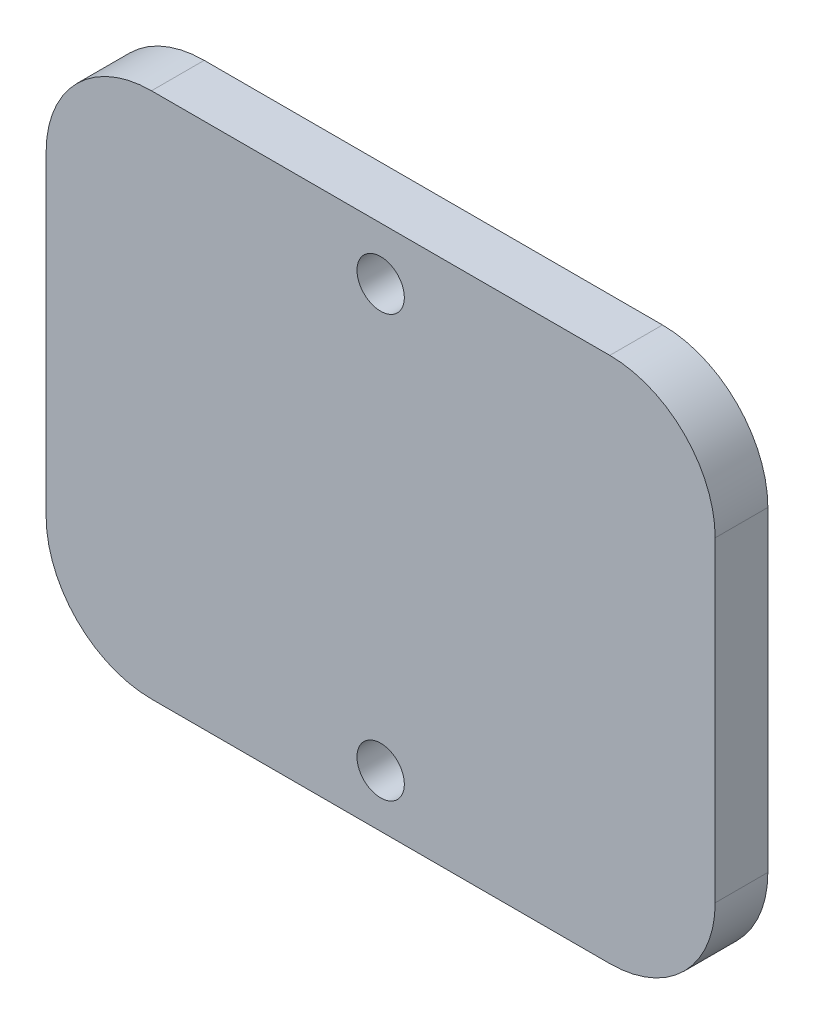
SolidWorks part; units mm, degrees
ref_plane "Front Plane" through (0, 0, 0) normal (0, 0, 1) x (1, 0, 0)
ref_plane "Top Plane" through (0, 0, 0) normal (0, 1, 0) x (1, 0, 0)
ref_plane "Right Plane" through (0, 0, 0) normal (1, 0, 0) x (0, 0, -1)
sketch "Sketch1" plane through (0, 0, 0) normal (0, 0, 1) x (1, 0, 0)
  line L1 (-31.75, -25) -> (31.75, -25)
  line L2 (-31.75, -25) -> (-31.75, 25)
  line L3 (-31.75, 25) -> (31.75, 25)
  line L4 (31.75, -25) -> (31.75, 25)
  line L5 (-31.75, -25) -> (31.75, 25) construction
  line L6 (-31.75, 25) -> (31.75, -25) construction
  point P0 (0, 0)
  dimension "D1" = 50
  dimension "D2" = 63.5
extrude "Boss-Extrude1" add sketch "Sketch1" along normal blind 5
fillet "Fillet1" radius 10 4 edges at (-31.75, -25, 2.5) (31.75, -25, 2.5) (31.75, 25, 2.5) (-31.75, 25, 2.5)
sketch "Sketch2" plane through (0, 0, 5) normal (0, 0, 1) x (1, 0, 0)
  line L0 (0, 0) -> (-24.2043, 30.1725) construction
  line L1 (-24.2043, -30.1725) -> (24.2043, -30.1725) construction
  line L2 (-24.2043, -30.1725) -> (-24.2043, 30.1725) construction
  line L3 (-24.2043, 30.1725) -> (24.2043, 30.1725) construction
  line L4 (24.2043, -30.1725) -> (24.2043, 30.1725) construction
  line L5 (-24.2043, -30.1725) -> (24.2043, 30.1725) construction
  line L6 (-24.2043, 30.1725) -> (24.2043, -30.1725) construction
  line L7 (-24.2043, 30.1725) -> (24.2043, 30.1725) construction
  line L8 (24.2043, 30.1725) -> (0, 0) construction
  line L9 (24.2043, -30.1725) -> (0, 0) construction
  line L10 (24.2043, 30.1725) -> (24.2043, -30.1725)
  line L11 (-24.2043, -30.1725) -> (0, 0) construction
  line L12 (0, 3.1962) -> (-20.0359, 28.1725)
  line L13 (-20.0359, 28.1725) -> (20.0359, 28.1725)
  line L14 (20.0359, 28.1725) -> (0, 3.1962)
  line L15 (-2.564, 0) -> (-22.2043, 24.4831)
  line L16 (-22.2043, -24.4831) -> (-22.2043, 24.4831)
  line L17 (-22.2043, -24.4831) -> (-2.564, 0)
  line L18 (0, 0) -> (24.2043, 30.1725) construction
  line L19 (2.564, 0) -> (22.2043, 24.4831)
  line L20 (22.2043, 24.4831) -> (22.2043, -24.4831)
  line L21 (22.2043, -24.4831) -> (2.564, 0)
  line L22 (-24.2043, -30.1725) -> (24.2043, -30.1725) construction
  line L23 (-20.0359, -28.1725) -> (0, -3.1962)
  line L24 (20.0359, -28.1725) -> (0, -3.1962)
  line L25 (-20.0359, -28.1725) -> (20.0359, -28.1725)
  point P0 (0, 0)
  dimension "D1" = 48.4086
  dimension "D2" = 2
  dimension "D3" = 2
  dimension "D4" = 2
  dimension "D5" = 2
extrude "Cut-Extrude2" [suppressed] cut sketch "Sketch2" against normal through all contours L14 L13 L12 | L16 L17 L15 | L23 L25 L24 | L21 L20 L19
fillet "Fillet2" [suppressed] radius 2
sketch "Sketch9" plane through (0, 0, 5) normal (0, 0, 1) x (1, 0, 0)
  circle A0 centre (0, 20) radius 2.2479
  circle A1 centre (0, -20) radius 2.2479
  dimension "D2" = 4.4958
  dimension "D3" = 4.4958
  dimension "D4" = 20
  dimension "D1" = 20
extrude "Cut-Extrude3" cut sketch "Sketch9" against normal through all
